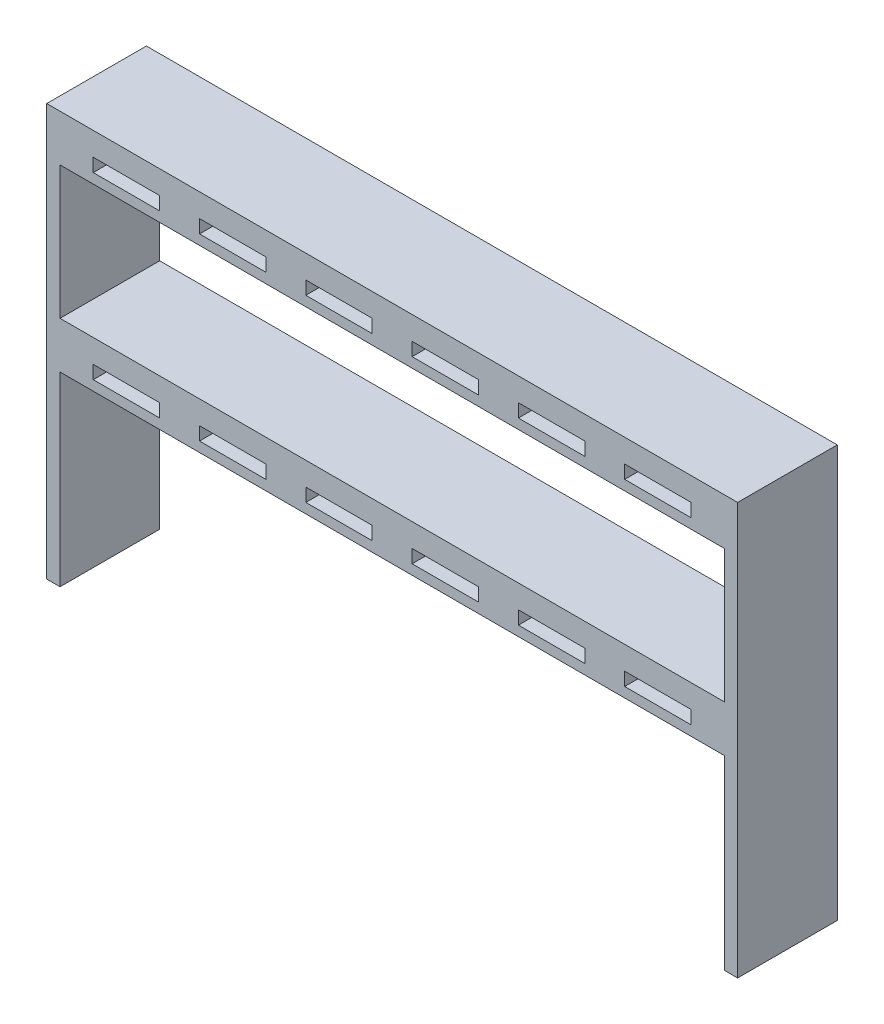
SolidWorks part; units mm, degrees
ref_plane "Front Plane" through (0, 0, 0) normal (0, 0, 1) x (1, 0, 0)
ref_plane "Top Plane" through (0, 0, 0) normal (0, 1, 0) x (1, 0, 0)
ref_plane "Right Plane" through (0, 0, 0) normal (1, 0, 0) x (0, 0, -1)
sketch "Sketch1" plane through (0, 0, 0) normal (0, 0, 1) x (1, 0, 0)
  line L0 (0, 0) -> (0, 33)
  line L1 (0, 60) -> (100, 60)
  line L2 (100, 60) -> (100, 35)
  line L3 (-2, 0) -> (-2, 62)
  line L4 (-2, 62) -> (102, 62)
  line L5 (102, 62) -> (102, 0)
  line L6 (-2, 0) -> (0, 0)
  line L7 (100, 0) -> (102, 0)
  line L8 (0, 35) -> (100, 35)
  line L9 (0, 33) -> (100, 33)
  line L10 (100, 33) -> (100, 0)
  line L11 (0, 35) -> (0, 60)
  line L12 (100, 60) -> (100, 0) construction
  line L14 (0, 0) -> (0, 60) construction
  dimension "D1" = 60
  dimension "D2" = 100
  dimension "D4" = 25
  dimension "D3" = 2
  dimension "D5" = 2
extrude "Boss-Extrude1" add sketch "Sketch1" along normal blind 15
sketch "Sketch2" plane through (0, 0, 15) normal (0, 0, -1) x (-1, 0, 0)
  line L0 (-100, 60) -> (0, 60) construction
  line L1 (0, 60) -> (-100, 60)
  line L2 (0, 60) -> (0, 55)
  line L3 (0, 55) -> (-100, 55)
  line L4 (-100, 60) -> (-100, 55)
  line L5 (-100, 35) -> (-100, 60) construction
  line L7 (0, 60) -> (0, 35) construction
  line L8 (-79, 56.5) -> (-79, 58.5)
  line L9 (-95, 56.5) -> (-85, 56.5)
  line L10 (-95, 56.5) -> (-95, 58.5)
  line L11 (-95, 58.5) -> (-85, 58.5)
  line L12 (-85, 56.5) -> (-85, 58.5)
  line L13 (-79, 58.5) -> (-69, 58.5)
  line L14 (-69, 56.5) -> (-69, 58.5)
  line L15 (-79, 56.5) -> (-69, 56.5)
  line L16 (-63, 56.5) -> (-63, 58.5)
  line L17 (-63, 58.5) -> (-53, 58.5)
  line L18 (-53, 56.5) -> (-53, 58.5)
  line L19 (-63, 56.5) -> (-53, 56.5)
  line L20 (-47, 56.5) -> (-47, 58.5)
  line L21 (-47, 58.5) -> (-37, 58.5)
  line L22 (-37, 56.5) -> (-37, 58.5)
  line L23 (-47, 56.5) -> (-37, 56.5)
  line L24 (-31, 56.5) -> (-31, 58.5)
  line L25 (-31, 58.5) -> (-21, 58.5)
  line L26 (-21, 56.5) -> (-21, 58.5)
  line L27 (-31, 56.5) -> (-21, 56.5)
  line L28 (-15, 56.5) -> (-15, 58.5)
  line L29 (-15, 58.5) -> (-5, 58.5)
  line L30 (-5, 56.5) -> (-5, 58.5)
  line L31 (-15, 56.5) -> (-5, 56.5)
  line L32 (0, 33) -> (-100, 33)
  line L33 (0, 33) -> (0, 28)
  line L34 (0, 28) -> (-100, 28)
  line L35 (-100, 33) -> (-100, 28)
  line L36 (-79, 29.5) -> (-79, 31.5)
  line L37 (-95, 29.5) -> (-85, 29.5)
  line L38 (-95, 29.5) -> (-95, 31.5)
  line L39 (-95, 31.5) -> (-85, 31.5)
  line L40 (-85, 29.5) -> (-85, 31.5)
  line L41 (-79, 31.5) -> (-69, 31.5)
  line L42 (-69, 29.5) -> (-69, 31.5)
  line L43 (-79, 29.5) -> (-69, 29.5)
  line L44 (-63, 29.5) -> (-63, 31.5)
  line L45 (-63, 31.5) -> (-53, 31.5)
  line L46 (-53, 29.5) -> (-53, 31.5)
  line L47 (-63, 29.5) -> (-53, 29.5)
  line L48 (-47, 29.5) -> (-47, 31.5)
  line L49 (-47, 31.5) -> (-37, 31.5)
  line L50 (-37, 29.5) -> (-37, 31.5)
  line L51 (-47, 29.5) -> (-37, 29.5)
  line L52 (-31, 29.5) -> (-31, 31.5)
  line L53 (-31, 31.5) -> (-21, 31.5)
  line L54 (-21, 29.5) -> (-21, 31.5)
  line L55 (-31, 29.5) -> (-21, 29.5)
  line L56 (-15, 29.5) -> (-15, 31.5)
  line L57 (-15, 31.5) -> (-5, 31.5)
  line L58 (-5, 29.5) -> (-5, 31.5)
  line L59 (-15, 29.5) -> (-5, 29.5)
  dimension "D1" = 5
  dimension "D2" = 1.5
  dimension "D3" = 1.5
  dimension "D4" = 5
  dimension "D5" = 10
  dimension "D6" = 6
  dimension "D7" = 2
extrude "Boss-Extrude2" add sketch "Sketch2" along normal blind 2
